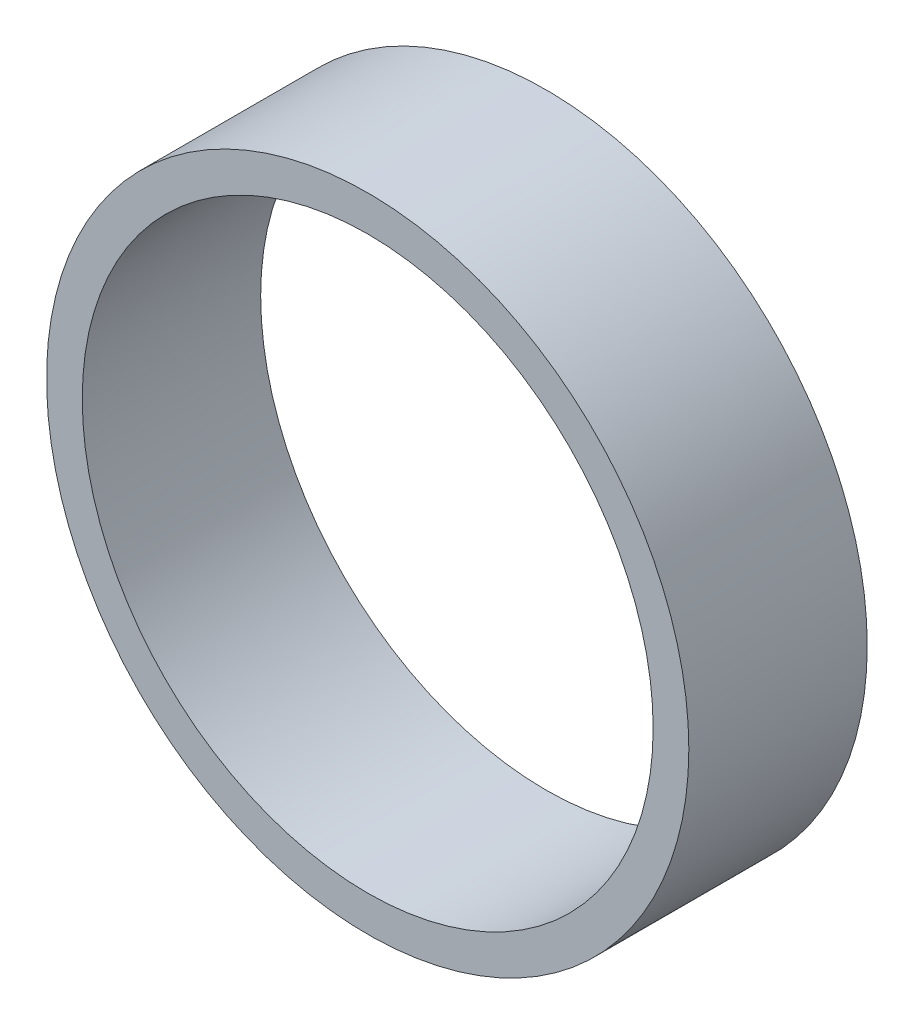
SolidWorks part; units mm, degrees
ref_plane "前视基准面" through (0, 0, 0) normal (0, 0, 1) x (1, 0, 0)
ref_plane "上视基准面" through (0, 0, 0) normal (0, 1, 0) x (1, 0, 0)
ref_plane "右视基准面" through (0, 0, 0) normal (1, 0, 0) x (0, 0, -1)
sketch "草图1" plane through (0, 0, 0) normal (0, 0, 1) x (1, 0, 0)
  circle A0 centre (0, 0) radius 1.8
  circle A1 centre (0, 0) radius 1.6
  dimension "D1" = 3.6
  dimension "D2" = 0.2
extrude "凸台-拉伸1" add sketch "草图1" along normal blind 1
